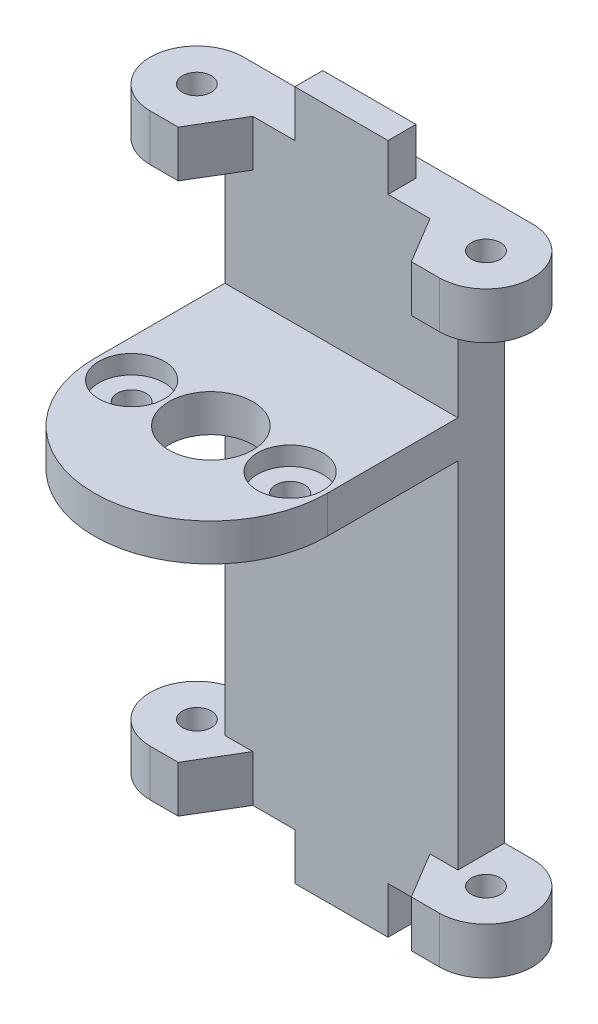
SolidWorks part; units mm, degrees
ref_plane "Front Plane" through (0, 0, 0) normal (0, 0, 1) x (1, 0, 0)
ref_plane "Top Plane" through (0, 0, 0) normal (0, 1, 0) x (1, 0, 0)
ref_plane "Right Plane" through (0, 0, 0) normal (1, 0, 0) x (0, 0, -1)
sketch "Sketch11" plane through (0, 0, 51.65) normal (0, -1, 0) x (1, 0, 0)
  line L0 (12.5, 85.5) -> (12.5, 71.5)
  line L1 (-12.5, 85.5) -> (-12.5, 71.5)
  line L3 (0, 71.5) -> (0, 85.5) construction
  line L6 (-12.5, 71.5) -> (12.5, 71.5)
  line L7 (-8.5, 85.5) -> (8.5, 85.5) construction
  circle A0 centre (-8.5, 85.5) radius 1.55
  circle A1 centre (8.5, 85.5) radius 1.55
  circle A4 centre (0, 85.5) radius 4.5
  arc A5 (-12.5, 85.5) -> (12.5, 85.5) centre (0, 85.5) cw
  point P15 (0, 85.5)
extrude "Boss-Extrude1" add sketch "Sketch11" along normal blind 4
sketch "Sketch12" plane through (0, 0, 123.15) normal (0, 0, -1) x (-1, 0, 0)
  line L0 (-12.5, 0) -> (-12.5, 17)
  line L1 (12.5, 0) -> (12.5, 17)
  line L3 (-12.5, 0) -> (-12.5, -4)
  line L4 (-12.5, -4) -> (-12.5, -47)
  line L5 (12.5, 0) -> (12.5, -4)
  line L6 (12.5, -4) -> (12.5, -47)
  line L20 (-12.5, 17) -> (12.5, 17)
  line L21 (-12.5, -47) -> (12.5, -47)
extrude "Boss-Extrude2" add sketch "Sketch12" along normal blind 5
sketch "Sketch13" plane through (0, 0, 0) normal (0, 1, 0) x (1, 0, 0)
  circle A0 centre (-8.5, -137.15) radius 3.5
  circle A1 centre (8.5, -137.15) radius 3.5
extrude "Cut-Extrude1" cut sketch "Sketch13" against normal blind 2
ref_plane "Plane1" through (0, 17, 0) normal (0, 1, 0) x (1, 0, 0)
sketch "Sketch14" plane through (0, 17, 0) normal (0, 1, 0) x (1, 0, 0)
  line L0 (12.5, -123.15) -> (15.5, -123.15) construction
  line L1 (-12.5, -137.15) -> (-12.5, -123.15) construction
  line L2 (-12.5, -123.15) -> (-15.5, -123.15) construction
  line L4 (12.5, -123.15) -> (12.5, -137.15) construction
  line L6 (15.5, -118.15) -> (-15.5, -118.15)
  line L7 (-15.5, -128.15) -> (-12.5, -128.15)
  line L11 (12.5, -128.15) -> (15.5, -128.15)
  line L12 (-12.5, -128.15) -> (-9.5, -123.15)
  line L13 (12.5, -128.15) -> (9.5, -123.15)
  line L15 (-12.5, -123.15) -> (12.5, -123.15) construction
  line L16 (9.5, -123.15) -> (-9.5, -123.15)
  arc A0 (-15.5, -118.15) -> (-15.5, -128.15) centre (-15.5, -123.15) ccw
  circle A1 centre (-15.5, -123.15) radius 1.55
  circle A2 centre (15.5, -123.15) radius 1.55
  arc A3 (15.5, -118.15) -> (15.5, -128.15) centre (15.5, -123.15) cw
extrude "Boss-Extrude3" add sketch "Sketch14" against normal blind 5
ref_plane "Plane2" through (0, -47, 0) normal (0, -1, 0) x (-1, 0, 0)
sketch "Sketch15" plane through (0, -47, 0) normal (0, -1, 0) x (-1, 0, 0)
  line L0 (15.5, -128.15) -> (12.5, -128.15) construction
  line L1 (15.5, -118.15) -> (-15.5, -118.15)
  line L2 (-15.5, -128.15) -> (-12.5, -128.15)
  line L3 (-12.5, -128.15) -> (-9.5, -123.15)
  line L5 (15.5, -128.15) -> (12.5, -128.15)
  line L6 (12.5, -128.15) -> (9.5, -123.15)
  line L8 (9.5, -123.15) -> (-9.5, -123.15)
  circle A0 centre (15.5, -123.15) radius 1.55
  circle A1 centre (-15.5, -123.15) radius 1.55
  arc A2 (15.5, -118.15) -> (15.5, -128.15) centre (15.5, -123.15) cw
  arc A3 (-15.5, -118.15) -> (-15.5, -128.15) centre (-15.5, -123.15) ccw
  arc A4 (-15.5, -118.15) -> (-15.5, -128.15) centre (-15.5, -123.15) ccw construction
extrude "Boss-Extrude4" add sketch "Sketch15" against normal blind 5
sketch "Sketch16" plane through (0, -47, 0) normal (0, -1, 0) x (1, 0, 0)
  line L0 (-5, 123.15) -> (5, 123.15)
  line L1 (-5, 123.15) -> (-5, 120.15)
  line L2 (-12.5, 123.15) -> (12.5, 123.15) construction
  line L5 (-5, 120.15) -> (5, 120.15)
  line L6 (5, 123.15) -> (5, 120.15)
  point P3 (0, 123.15)
extrude "Boss-Extrude5" add sketch "Sketch16" along normal blind 5
sketch "Sketch17" plane through (0, 17, 0) normal (0, 1, 0) x (1, 0, 0)
  line L0 (-5, -123.15) -> (5, -123.15)
  line L1 (-9.5, -123.15) -> (9.5, -123.15) construction
  line L2 (-5, -123.15) -> (-5, -120.15)
  line L3 (-5, -120.15) -> (5, -120.15)
  line L4 (5, -120.15) -> (5, -123.15)
  point P5 (0, -123.15)
extrude "Boss-Extrude6" add sketch "Sketch17" along normal blind 5
